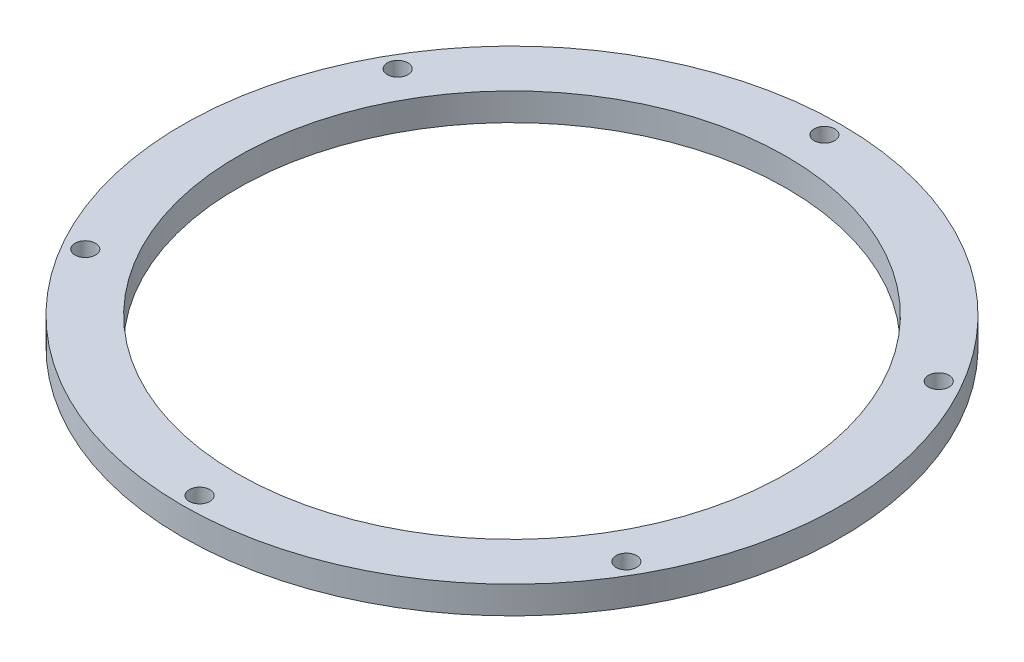
SolidWorks part; units mm, degrees
ref_plane "前视基准面" through (0, 0, 0) normal (0, 0, 1) x (1, 0, 0)
ref_plane "上视基准面" through (0, 0, 0) normal (0, 1, 0) x (1, 0, 0)
ref_plane "右视基准面" through (0, 0, 0) normal (1, 0, 0) x (0, 0, -1)
other "Configuration Table"
sketch "草图1" plane through (0, 0, 0) normal (0, 1, 0) x (1, 0, 0)
  line L0 (0, 0) -> (40, 0) construction
  line L1 (40, 0) -> (48, 0) construction
  line L2 (0, 0) -> (0, 40) construction
  line L3 (0, 40) -> (0, 48) construction
  line L9 (-40, 0) -> (-43, 0) construction
  line L10 (0, -48) -> (0, -43) construction
  circle A0 centre (0, 0) radius 40
  circle A2 centre (0, 0) radius 43 construction
  circle A4 centre (0, -45.5) radius 1.5
  circle A5 centre (-39.4042, -22.75) radius 1.5
  circle A6 centre (-39.4042, 22.75) radius 1.5
  circle A7 centre (0, 45.5) radius 1.5
  circle A8 centre (39.4042, 22.75) radius 1.5
  circle A9 centre (39.4042, -22.75) radius 1.5
  circle A10 centre (0, 0) radius 48
  point P31 (0, 0)
  dimension "D1" = 3
  dimension "D4" = 86
  dimension "D6" = 3
  dimension "D5" = 5
  dimension "D7" = 6
extrude "凸台-拉伸1" add sketch "草图1" along normal blind 4
